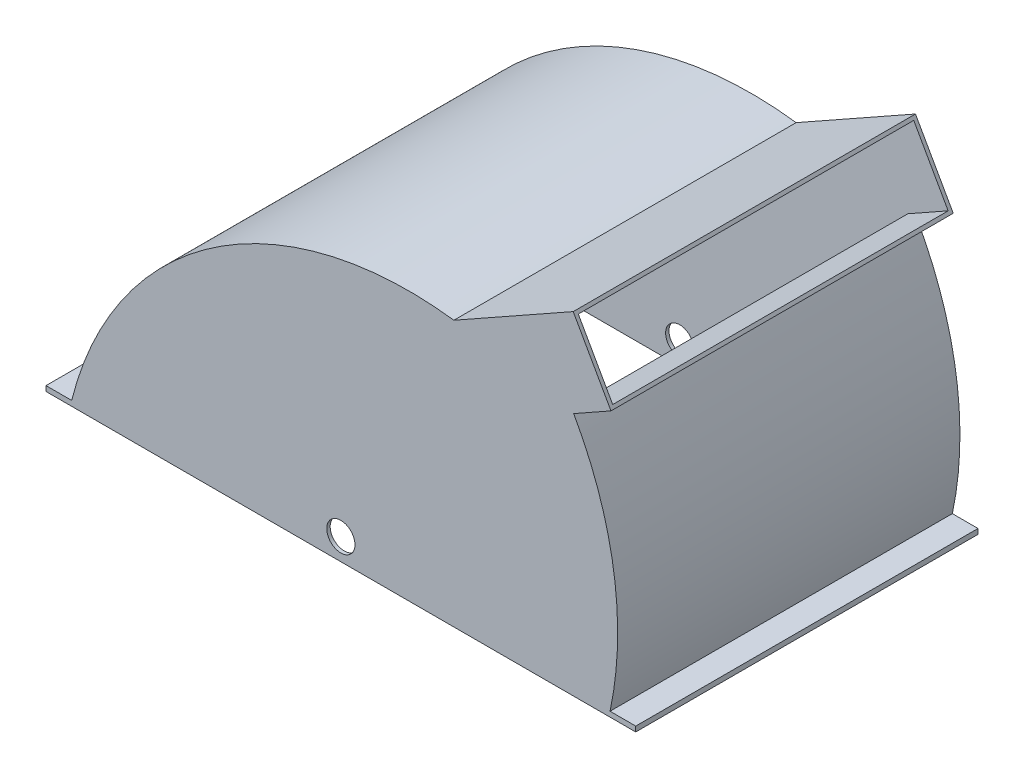
SolidWorks part; units mm, degrees
ref_plane "Front Plane" through (0, 0, 0) normal (0, 0, 1) x (1, 0, 0)
ref_plane "Top Plane" through (0, 0, 0) normal (0, 1, 0) x (1, 0, 0)
ref_plane "Right Plane" through (0, 0, 0) normal (1, 0, 0) x (0, 0, -1)
sketch "Sketch1" plane through (0, 0, 0) normal (0, 0, 1) x (1, 0, 0)
  line L0 (-157.3, 0) -> (157.3, 0) construction
  line L1 (-157.3, 0) -> (-172.3, 0)
  line L5 (157.3, 0) -> (172.3, 0)
  line L6 (0, 0) -> (0, 150) construction
  line L7 (-172.3, 0) -> (-172.3, -3)
  line L8 (-172.3, -3) -> (172.3, -3)
  line L9 (172.3, -3) -> (172.3, 0)
  line L10 (66.046, 152.2474) -> (135.767, 191.4774)
  line L11 (135.767, 191.4774) -> (157.8338, 152.2594)
  line L12 (157.8338, 152.2594) -> (136.046, 140)
  arc A2 (66.046, 152.2474) -> (-157.3, 0) centre (39.8417, -49.2583) ccw
  arc A3 (136.046, 140) -> (157.3, 0) centre (-38.2563, 41.9251) cw
  point P3 (0, 0)
  dimension "D5" = 314.6
  dimension "D11" = 45
  dimension "D3" = 200
  dimension "D4" = 140
  dimension "D6" = 15
  dimension "D7" = 70
  dimension "D8" = 25
  dimension "D9" = 80
  dimension "D10" = 3
  dimension "D12" = 150
extrude "Boss-Extrude1" add sketch "Sketch1" along normal mid plane 200
sketch "Sketch3" plane through (184.9506, 104.0663, 0) normal (0.8715, 0.4904, 0) x (0, 0, -1)
  line L0 (-100, 100.2982) -> (100, 100.2982) construction
  line L5 (-98, 98.2982) -> (98, 98.2982)
  line L6 (-98, 98.2982) -> (-98, 57.2982)
  line L7 (-98, 57.2982) -> (98, 57.2982)
  line L8 (98, 98.2982) -> (98, 57.2982)
  line L9 (-98, 98.2982) -> (98, 57.2982) construction
  line L10 (-98, 57.2982) -> (98, 98.2982) construction
  line L11 (-100, 55.2982) -> (100, 55.2982) construction
  line L12 (100, 55.2982) -> (100, 100.2982) construction
  line L13 (-100, 55.2982) -> (-100, 100.2982) construction
  point P0 (0, 77.7982)
  point P7 (0, 100.2982)
  dimension "D1" = 2
  dimension "D2" = 2
  dimension "D3" = 2
  dimension "D4" = 2
split line "Split Line1"
shell "Shell1" thickness 2
sketch "Sketch4" plane through (0, -2, 0) normal (0, -1, 0) x (1, 0, 0)
  line L4 (-170.3, -98) -> (-155.732, -98)
  line L5 (-155.732, -98) -> (-155.732, 98)
  line L6 (-155.732, 98) -> (-170.3, 98)
  line L7 (-170.3, 98) -> (-170.3, -98)
  line L8 (-170.3, -98) -> (-155.732, -98)
  line L9 (-155.732, -98) -> (-155.732, 98)
  line L10 (-155.732, 98) -> (-170.3, 98)
  line L11 (-170.3, 98) -> (-170.3, -98)
  line L12 (154.8099, -98) -> (170.3, -98)
  line L13 (170.3, -98) -> (170.3, 98)
  line L14 (170.3, 98) -> (154.8099, 98)
  line L15 (154.8099, 98) -> (154.8099, -98)
  line L16 (154.8099, -98) -> (170.3, -98)
  line L17 (170.3, -98) -> (170.3, 98)
  line L18 (170.3, 98) -> (154.8099, 98)
  line L19 (154.8099, 98) -> (154.8099, -98)
  dimension "D1" = 0
  dimension "D2" = 0
extrude "Boss-Extrude2" add sketch "Sketch4" along normal up to surface (1 mm away) up to face at (0, -3, 0)
sketch "Sketch5" plane through (0, 0, 100) normal (0, 0, 1) x (1, 0, 0)
  circle A0 centre (0, 9.6927) radius 8.25
  dimension "D1" = 16.5
extrude "Cut-Extrude1" cut sketch "Sketch5" against normal through all both and the other way through all
